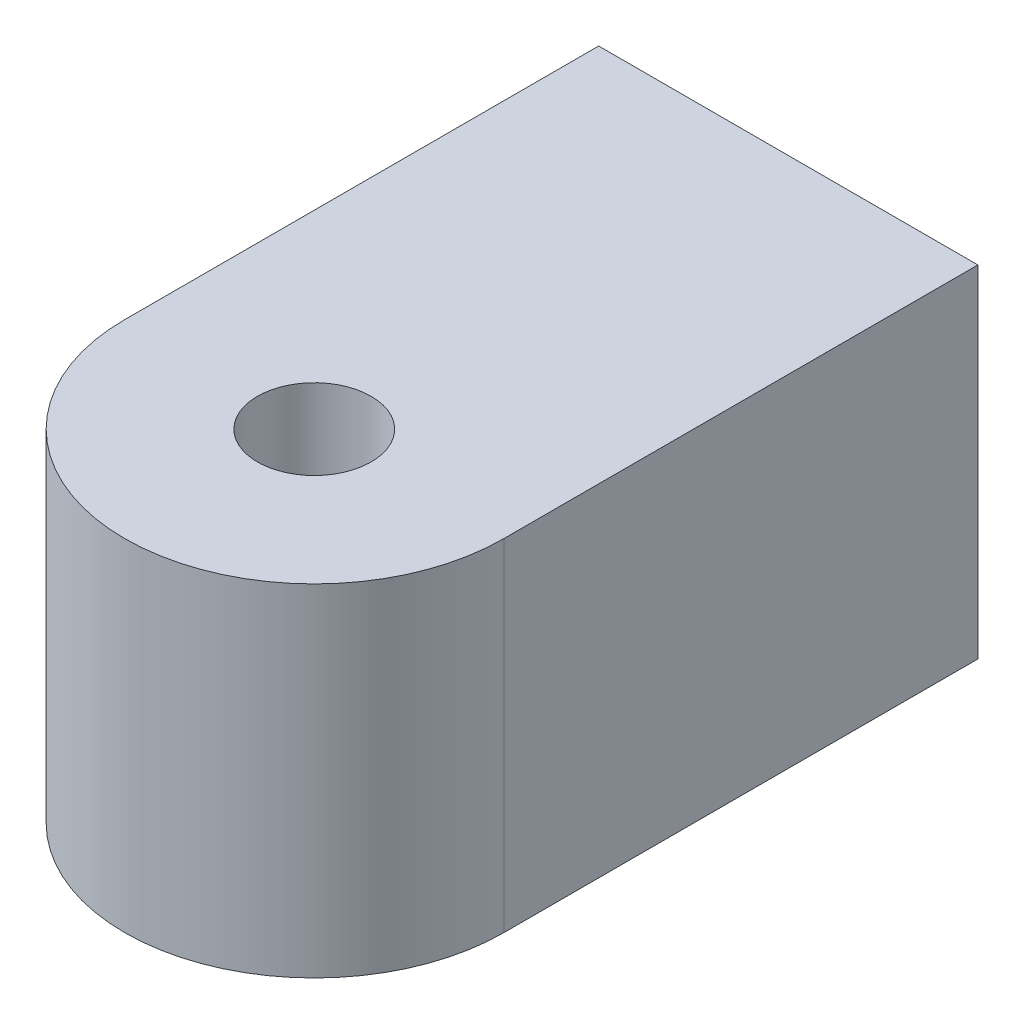
SolidWorks part; units mm, degrees
ref_plane "Front Plane" through (0, 0, 0) normal (0, 0, 1) x (1, 0, 0)
ref_plane "Top Plane" through (0, 0, 0) normal (0, 1, 0) x (1, 0, 0)
ref_plane "Right Plane" through (0, 0, 0) normal (1, 0, 0) x (0, 0, -1)
sketch "Sketch2" plane through (0, 0, 0) normal (0, 1, 0) x (1, 0, 0)
  circle A0 centre (0, 0) radius 50
  circle A1 centre (0, 0) radius 15
  dimension "D1" = 100
  dimension "D2" = 30
extrude "Boss-Extrude1" add sketch "Sketch2" along normal blind 90
sketch "Sketch3" plane through (0, 90, 0) normal (0, 1, 0) x (1, 0, 0)
  line L0 (-50, 0) -> (-50, 125)
  line L1 (-50, 125) -> (50, 125)
  line L2 (50, 125) -> (50, 0)
  arc A0 (50, 0) -> (-50, 0) centre (0, 0) ccw
  point P7 (50, 151.2744)
  dimension "D1" = 100
  dimension "D2" = 175
extrude "Boss-Extrude2" add sketch "Sketch3" against normal up to surface (90 mm away) up to face at (0, 0, 50)
sketch "Sketch4" plane through (0, 0, -125) normal (0, 0, -1) x (-1, 0, 0)
  line L0 (0, 90) -> (0, 0) construction
  line L1 (-50, 90) -> (50, 90) construction
  line L2 (50, 0) -> (-50, 0) construction
  line L3 (50, 45) -> (-50, 45) construction
  line L4 (50, 0) -> (50, 90) construction
  line L5 (-50, 0) -> (-50, 90) construction
  circle A0 centre (0, 47.9762) radius 15
  dimension "D1" = 30
extrude "Boss-Extrude3" add sketch "Sketch4" along normal blind 25
